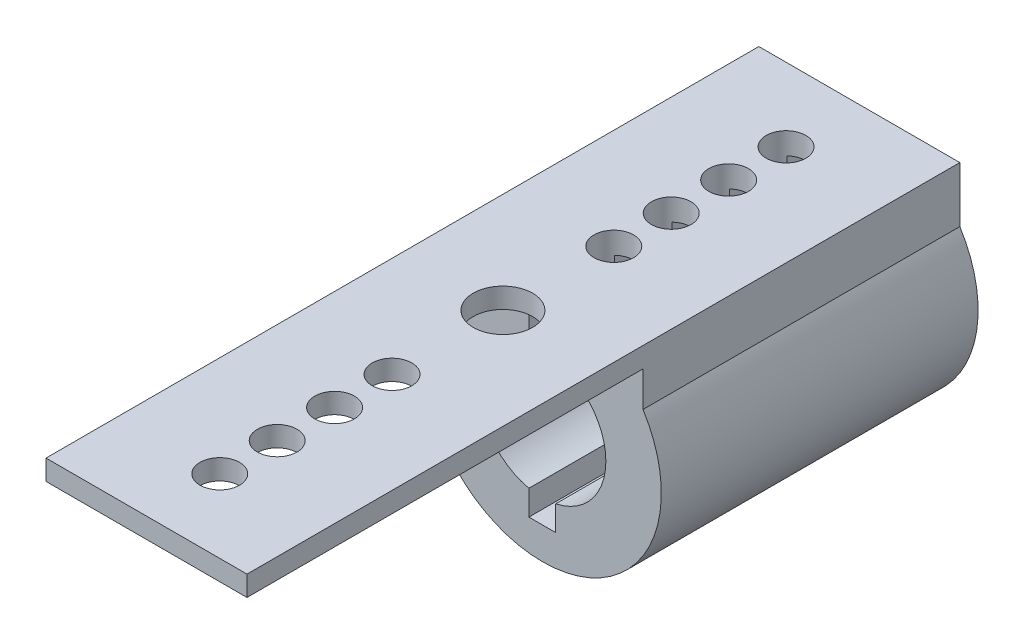
SolidWorks part; units mm, degrees
ref_plane "Front Plane" through (0, 0, 0) normal (0, 0, 1) x (1, 0, 0)
ref_plane "Top Plane" through (0, 0, 0) normal (0, 1, 0) x (1, 0, 0)
ref_plane "Right Plane" through (0, 0, 0) normal (1, 0, 0) x (0, 0, -1)
sketch "Sketch1" plane through (0, 0, 0) normal (0, 0, 1) x (1, 0, 0)
  circle A0 centre (0, 0) radius 3.2
  circle A1 centre (0, 0) radius 6
  dimension "D1" = 6.4
  dimension "D2" = 12
extrude "Boss-Extrude1" add sketch "Sketch1" along normal blind 16
sketch "Sketch2" plane through (0, 0, 0) normal (0, 0, 1) x (1, 0, 0)
  line L0 (0, 0) -> (0, 6) construction
  line L1 (0, 6) -> (0, 3.2) construction
  line L2 (0, 3.2) -> (5.0754, 3.2) construction
  line L3 (5.0754, 3.2) -> (-5.0754, 3.2) construction
  line L5 (-5.0754, 3.2) -> (5.0754, 3.2)
  line L6 (-5.0754, 3.2) -> (-5.0754, 6)
  line L7 (-5.0754, 6) -> (5.0754, 6)
  line L8 (5.0754, 3.2) -> (5.0754, 6)
  circle A0 centre (0, 0) radius 6 construction
  circle A1 centre (0, 0) radius 3.2 construction
extrude "Boss-Extrude2" add sketch "Sketch2" along normal blind 16
sketch "Sketch3" plane through (0, 0, 0) normal (0, 0, 1) x (1, 0, 0)
  line L0 (0, -6.6461) -> (0, 6) construction
  line L1 (5.0754, 6) -> (-5.0754, 6) construction
  line L3 (-0.6872, 4.8987) -> (0.6676, 4.8987)
  line L4 (-0.6872, 4.8987) -> (-0.6872, -4.3882)
  line L5 (-0.6872, -4.3882) -> (0.6676, -4.3882)
  line L6 (0.6676, 4.8987) -> (0.6676, -4.3882)
extrude "Cut-Extrude1" cut sketch "Sketch3" against normal blind 1 and the other way blind 16
sketch "Sketch4" plane through (0, 0, 0) normal (0, 0, 1) x (1, 0, 0)
  line L1 (5.0754, 3.2) -> (5.0754, 6) construction
  line L2 (-5.0754, 6) -> (5.0754, 6)
  line L3 (-5.0754, 6) -> (-5.0754, 4.9772)
  line L4 (-5.0754, 4.9772) -> (5.0754, 4.9772)
  line L5 (5.0754, 6) -> (5.0754, 4.9772)
extrude "Boss-Extrude3" add sketch "Sketch4" along normal blind 36
sketch "Sketch5" plane through (0, 0, 0) normal (0, 1, 0) x (1, 0, 0)
  line L0 (-5.0754, 0) -> (5.0754, -36) construction
  line L1 (5.0754, -36) -> (-5.0754, -36) construction
  line L2 (-5.0754, -36) -> (5.0754, 0) construction
  circle A0 centre (0, -18) radius 1.5
  dimension "D1" = 3
extrude "Cut-Extrude2" cut sketch "Sketch5" along normal blind 11
sketch "Sketch6" plane through (0, 0, 0) normal (0, 1, 0) x (1, 0, 0)
  line L0 (0, 0) -> (0, -36) construction
  line L1 (5.0754, -36) -> (-5.0754, -36) construction
  line L2 (0, -36) -> (0, -18) construction
  line L3 (0, -18) -> (5.0754, -18) construction
  line L4 (5.0754, -36) -> (5.0754, 0) construction
  line L5 (5.0754, -18) -> (-5.0754, -18) construction
  line L6 (-5.0754, -36) -> (-5.0754, 0) construction
  circle A0 centre (0, -12.4) radius 1
  circle A1 centre (0, -9.5) radius 1
  circle A2 centre (0, -6.6) radius 1
  circle A3 centre (0, -3.7) radius 1
  circle A4 centre (0, -23.6) radius 1
  circle A5 centre (0, -26.5) radius 1
  circle A6 centre (0, -29.4) radius 1
  circle A7 centre (0, -32.3) radius 1
  point P30 (0, -18)
  dimension "D1" = 2
  dimension "D4" = 2
  dimension "D6" = 2
  dimension "D8" = 2
  dimension "D2" = 5.6
  dimension "D3" = 2.9
  dimension "D5" = 2.9
  dimension "D7" = 2.9
  dimension "D9" = 2
extrude "Cut-Extrude3" cut sketch "Sketch6" against normal blind 0.1 and the other way blind 11
